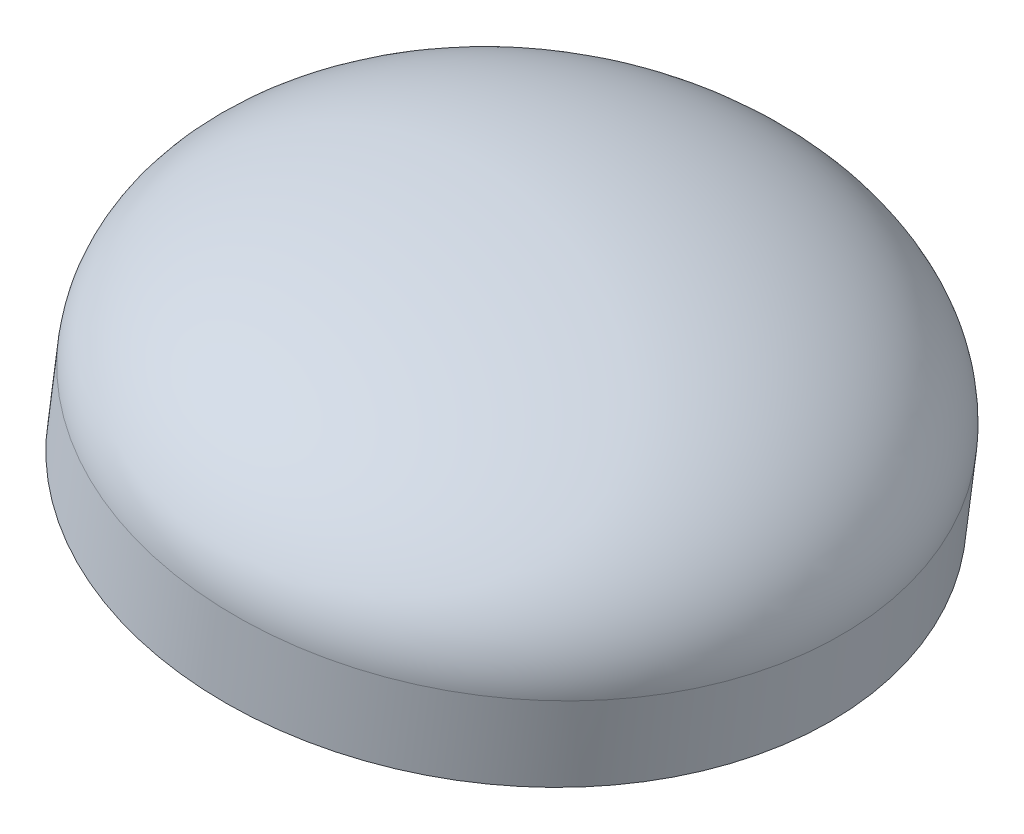
SolidWorks part; units mm, degrees
material "Простая углеродистая сталь"
ref_plane "Спереди" through (0, 0, 0) normal (0, 0, 1) x (1, 0, 0)
ref_plane "Сверху" through (0, 0, 0) normal (0, 1, 0) x (1, 0, 0)
ref_plane "Справа" through (0, 0, 0) normal (1, 0, 0) x (0, 0, -1)
sketch "Эскиз1" plane through (0, 0, 0) normal (0, 0, 1) x (1, 0, 0)
  line L0 (-227.9305, -25.4572) -> (-7.4178, -55.1282)
  line L1 (14.8355, 110.2564) -> (0, 0)
  line L2 (-220.5128, 29.671) -> (-227.9305, -25.4572)
  line L3 (0, 0) -> (-7.4178, -55.1282)
  ellipse E0 centre (0, 0) end of major axis (-220.5128, 29.671) minor radius 111.25 (14.8355, 110.2564) -> (-220.5128, 29.671) ccw
revolve "Повернуть1" add sketch "Эскиз1" angle 360 about L1
shell "Оболочка1" thickness 2
